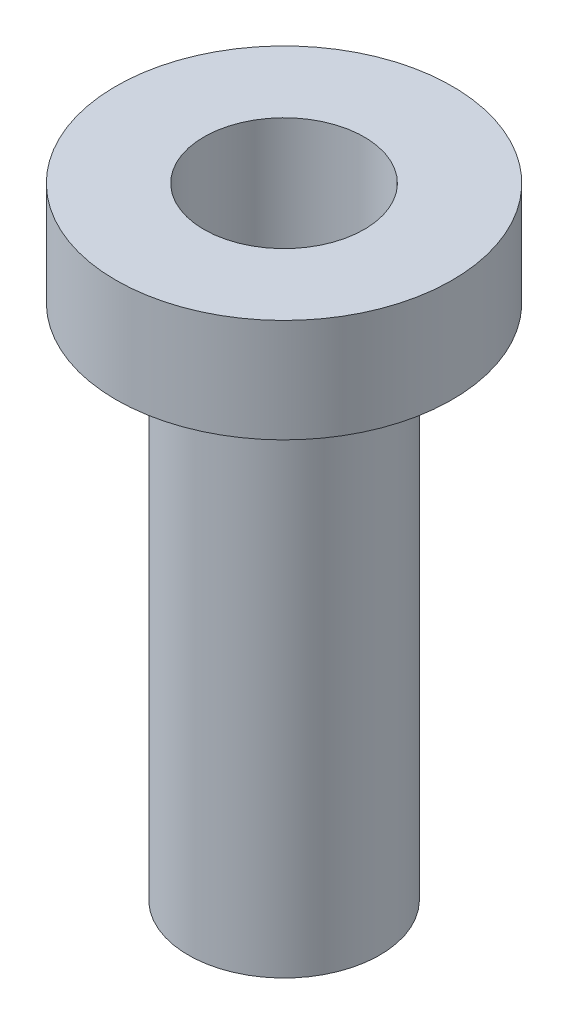
SolidWorks part; units mm, degrees
ref_plane "Front Plane" through (0, 0, 0) normal (0, 0, 1) x (1, 0, 0)
ref_plane "Top Plane" through (0, 0, 0) normal (0, 1, 0) x (1, 0, 0)
ref_plane "Right Plane" through (0, 0, 0) normal (1, 0, 0) x (0, 0, -1)
sketch "Sketch1" plane through (0, 0, 0) normal (0, 1, 0) x (1, 0, 0)
  circle A0 centre (0, 0) radius 3.25
extrude "Boss-Extrude1" add sketch "Sketch1" along normal blind 2
sketch "Sketch2" plane through (0, 0, 0) normal (0, -1, 0) x (-1, 0, 0)
  circle A0 centre (0, 0) radius 1.85
extrude "Boss-Extrude2" add sketch "Sketch2" along normal blind 10 contours A0
sketch "Sketch3" plane through (0, 2, 0) normal (0, 1, 0) x (1, 0, 0)
  circle A0 centre (0, 0) radius 1.55
extrude "Cut-Extrude1" cut sketch "Sketch3" against normal through all
